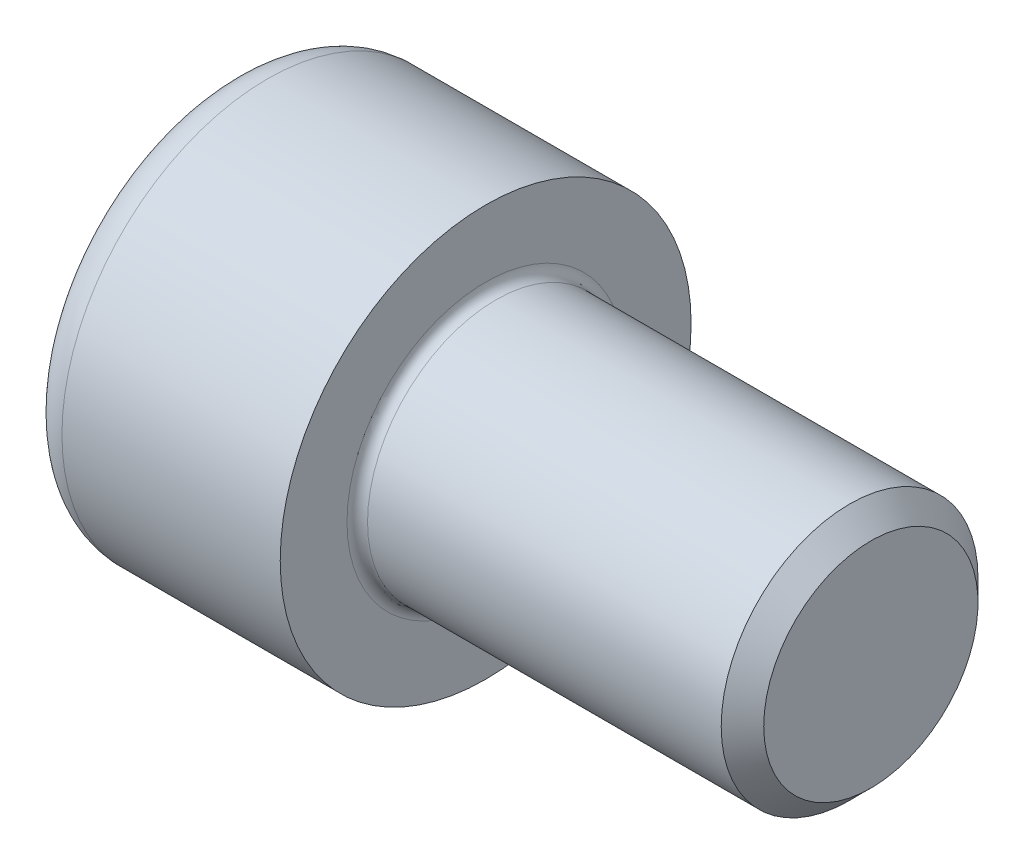
SolidWorks part; units mm, degrees
revolve "Base-Revolve" add sketch "BodySke"
sketch "BodySke" plane through (0, 0, 0) normal (0, 0, 1) x (1, 0, 0)
  line L0 (0, 0) -> (0, 8)
  line L1 (0, 8) -> (10, 8)
  line L2 (10, 8) -> (10, 5)
  line L3 (10, 5) -> (24.172, 5)
  line L4 (25, 4.172) -> (25, 0)
  line L5 (25, 0) -> (0, 0)
  line L6 (-31.75, 0) -> (127, 0) construction
  line L8 (25, 4.172) -> (24.172, 5)
  line L10 (25, -4.172) -> (24.172, -5) construction
  line L11 (11.5, 9.525) -> (11.5, 3.175) construction
  line L12 (15, 9.525) -> (15, 3.175) construction
  line L13 (-35, 9.525) -> (-35, 3.175) construction
  dimension "Head_ht" = 10
  dimension "Length" = 15
  dimension "Body_ch_ang" = 45
  dimension "Diameter" = 10
  dimension "Minor_dia" = 8.344
  dimension "Advance" = 1.5
  dimension "Thread_length" = 60
  dimension "Head_dia" = 16
cosmetic thread "ThreadCosmetic"
fillet "Fillet1" radius 0.4 1 edges at (10, 0, 5)
fillet "Fillet2" radius 1.5 1 edges at (0, 0, 8)
ref_plane "Plane1" through (0, 0, 0) normal (0, 0, 1) x (1, 0, 0)
ref_plane "Plane2" through (0, 0, 0) normal (0, 1, 0) x (1, 0, 0)
ref_plane "Plane3" through (0, 0, 0) normal (1, 0, 0) x (0, 0, -1)
other "Configuration Table"
sketch "Sketch2" plane through (0, 0, 0) normal (0, 0, 1) x (1, 0, 0)
  line L0 (0, 4.0575) -> (5, 4.0575)
  line L1 (5, 4.0575) -> (7.3426, 0)
  line L2 (-31.75, 0) -> (127, 0) construction
  line L3 (7.3426, 0) -> (0, 0)
  line L4 (0, 0) -> (0, 4.0575)
  line L6 (0, 0) -> (47.625, 0) construction
  dimension "D1" = 4.0575
  dimension "D2" = 60
  dimension "Depth" = 5
revolve "Hex-PreBroach" cut sketch "Sketch2" angle 360 about L6
sketch "Sketch3" plane through (0, 0, 0) normal (-1, 0, 0) x (0, 0.5, 0.866)
  line L0 (2.3426, 4.0575) -> (-2.3426, 4.0575)
  line L1 (-2.3426, 4.0575) -> (-4.6852, 0)
  line L2 (2.3426, 4.0575) -> (4.6852, 0)
  line L3 (2.3426, -4.0575) -> (4.6852, 0)
  line L4 (2.3426, -4.0575) -> (-2.3426, -4.0575)
  line L5 (-2.3426, -4.0575) -> (-4.6852, 0)
  dimension "D1" = 4.0575
  dimension "D2" = 4.0575
  dimension "Hex_size" = 8.115
extrude "Hex" cut sketch "Sketch3" against normal blind 5
sketch "ThdSchSke" plane through (0, 0, 0) normal (0, 0, 1) x (1, 0, 0)
  line L0 (9.5, -4.172) -> (8.9202, -5)
  line L1 (9.5, -4.172) -> (10.0798, -5)
  line L2 (10.0798, -5) -> (10.0798, -6.25)
  line L3 (-3.175, 0) -> (5.1513, 0) construction
  line L4 (0, 6.5) -> (0, -6.5) construction
  line L5 (10.0798, -6.25) -> (8.9202, -6.25)
  line L6 (8.9202, -6.25) -> (8.9202, -5)
  dimension "Thread_minor" = 8.344
  dimension "Diameter" = 10
  dimension "Start" = 9.5
revolve "ThreadSchematic" [suppressed] cut sketch "ThdSchSke" angle 360 about L3
pattern_linear "ThdSchPat" [suppressed]
equation "\"D2@Sketch3\" = \"Hex_size@Sketch3\" / 2"
equation "\"D1@Sketch3\" = \"Hex_size@Sketch3\" / 2"
equation "\"D1@Sketch2\" = \"Hex_size@Sketch3\" / 2"
equation "\"Thread_minor@ThreadCosmetic\"  =  \"Minor_dia@BodySke\""
equation "\"Depth@Sketch2\" =  \"Key_eng@Hex\""
equation "\"Thread_minor@ThdSchSke\"= \"Minor_dia@BodySke\""
equation "\"Diameter@ThdSchSke\" = \"Diameter@BodySke\""
equation "\"Overcut@ThdSchSke\" = \"Diameter@BodySke\" * 1.25"
equation "\"Start@ThdSchSke\" = \"Head_ht@BodySke\" + \"Length@BodySke\" - \"Thread_length@ThreadCosmetic\"  '---Non-countersunk---"
equation "\"Num_threads@ThdSchPat\" = int( \"Thread_length@ThreadCosmetic\" / \"Advance@BodySke\" + 0.999 )  + 1"
equation "\"Advance@ThdSchPat\" = \"Thread_length@ThreadCosmetic\" /  (\"Num_threads@ThdSchPat\" - 1) 'relax it"
equation "\"Num_threads@ThdSchPat\" = \"Num_threads@ThdSchPat\" - sgn( \"Num_threads@ThdSchPat\" - 1) '---chamfered tips only---"
